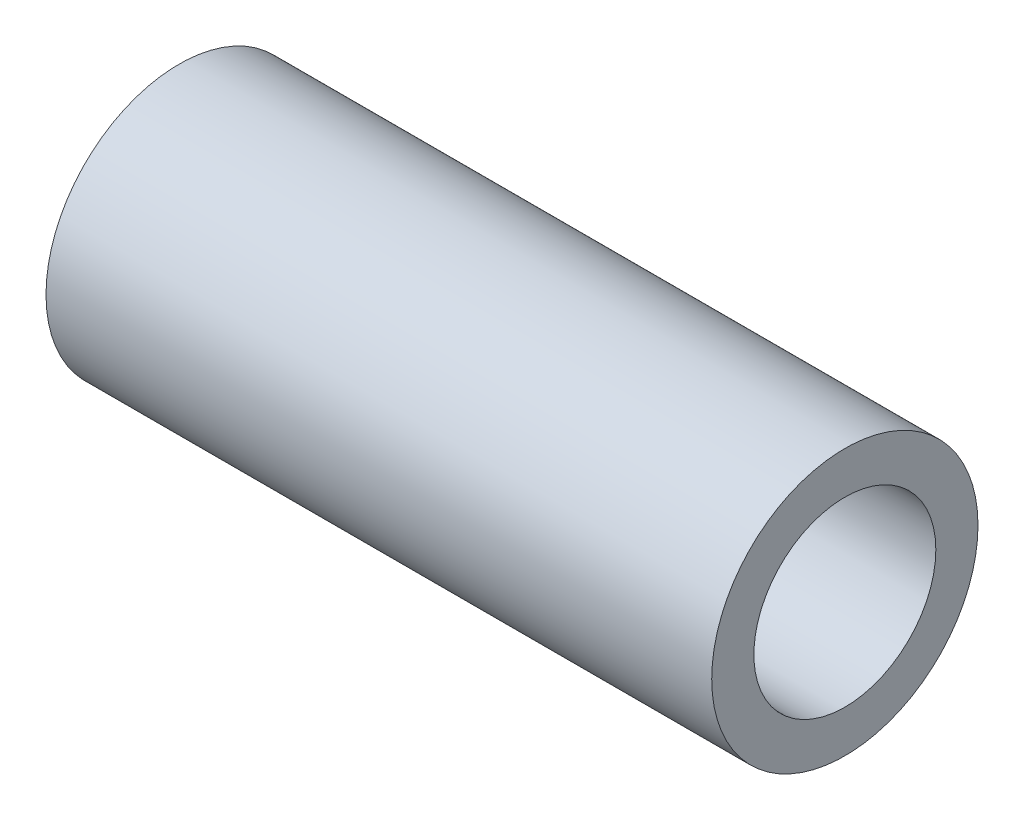
SolidWorks part; units mm, degrees
ref_plane "Front Plane" through (0, 0, 0) normal (1, 0, 0) x (0, 1, 0)
ref_plane "Top Plane" through (0, 0, 0) normal (0, 0, 1) x (0, 1, 0)
ref_plane "Right Plane" through (0, 0, 0) normal (0, 1, 0) x (-1, 0, 0)
sketch "Sketch1" plane through (0, 0, 0) normal (1, 0, 0) x (0, 1, 0)
  circle A0 centre (0, 0) radius 6
  circle A1 centre (0, 0) radius 4.1
  dimension "D1" = 12
  dimension "D2" = 8.2
extrude "Boss-Extrude1" add sketch "Sketch1" along normal blind 30
